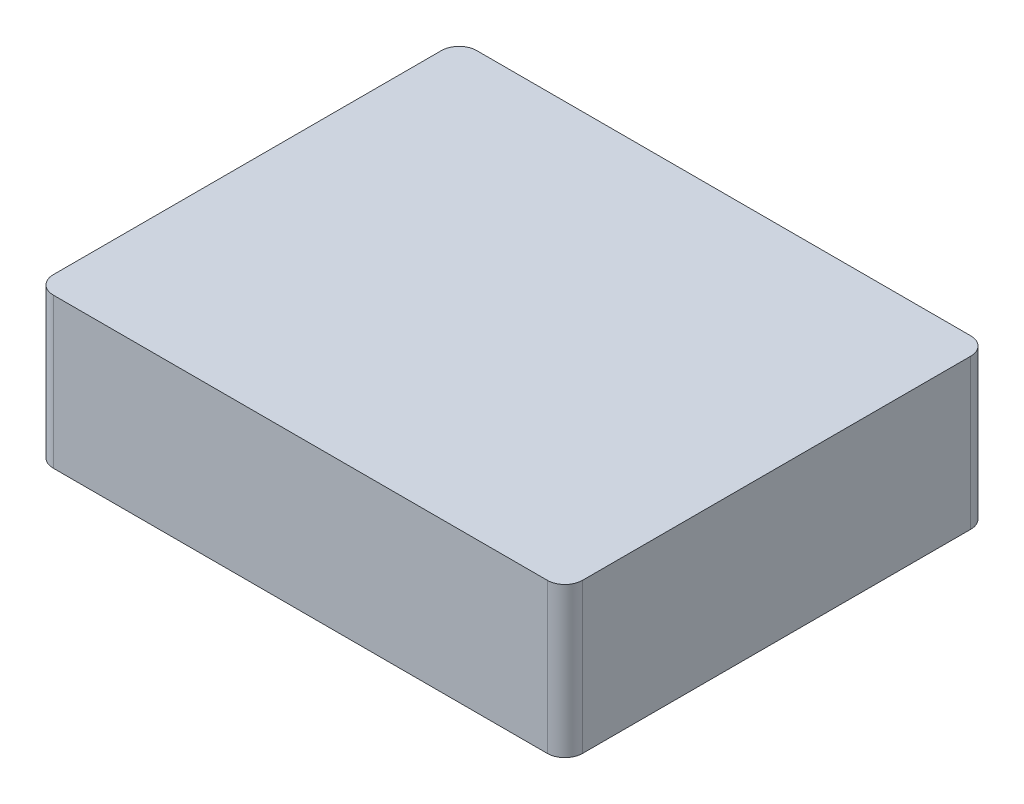
SolidWorks part; units mm, degrees
ref_plane "Front Plane" through (0, 0, 0) normal (0, 0, 1) x (1, 0, 0)
ref_plane "Top Plane" through (0, 0, 0) normal (0, 1, 0) x (1, 0, 0)
ref_plane "Right Plane" through (0, 0, 0) normal (1, 0, 0) x (0, 0, -1)
sketch "Sketch1" plane through (0, 0, 0) normal (0, 0, 1) x (1, 0, 0)
  line L1 (-7.2934, 4.4243) -> (22.7066, 4.4243)
  line L2 (-7.2934, 4.4243) -> (-7.2934, -4.0757)
  line L3 (-7.2934, -4.0757) -> (22.7066, -4.0757)
  line L4 (22.7066, 4.4243) -> (22.7066, -4.0757)
  dimension "D1" = 8.5
  dimension "D2" = 30
extrude "Boss-Extrude1" add sketch "Sketch1" along normal blind 24
fillet "Fillet1" radius 1 4 edges at (-7.2934, 0.1743, 0) (-7.2934, 0.1743, 24) (22.7066, 0.1743, 0) (22.7066, 0.1743, 24)
